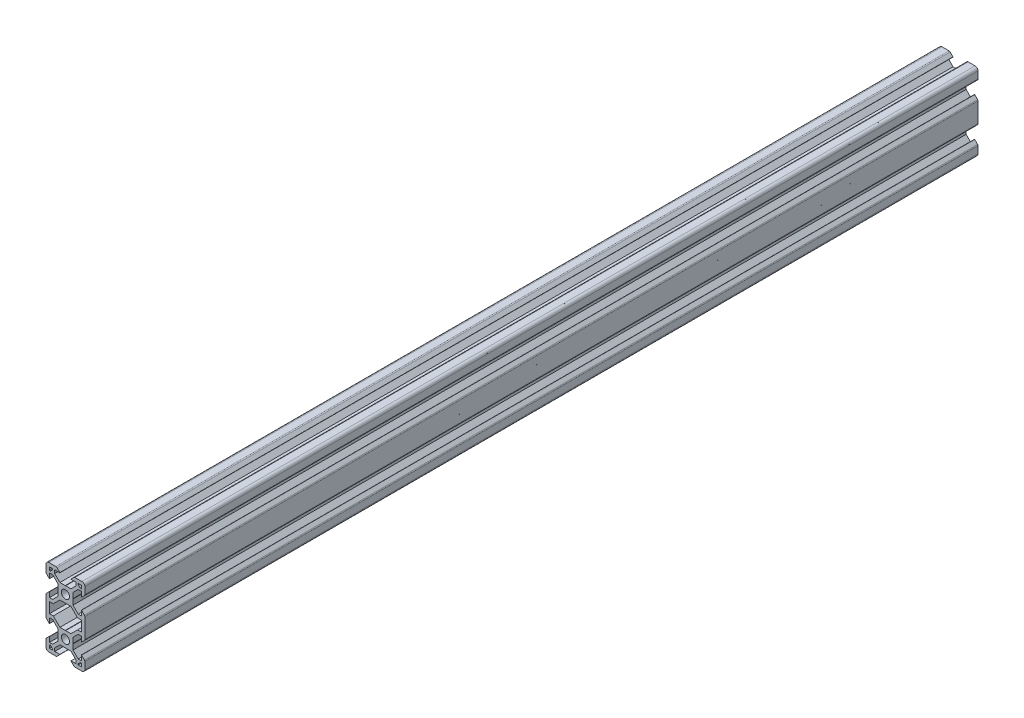
SolidWorks part; units mm, degrees
ref_plane "Front Plane" through (0, 0, 0) normal (0, 0, 1) x (1, 0, 0)
ref_plane "Top Plane" through (0, 0, 0) normal (0, 1, 0) x (1, 0, 0)
ref_plane "Right Plane" through (0, 0, 0) normal (1, 0, 0) x (0, 0, -1)
sketch "Sketch1" plane through (0, 0, 0) normal (0, 0, 1) x (1, 0, 0)
  line L0 (-8.2, 2.8875) -> (-8.2, 5.4975)
  line L3 (-4.9072, 9.9975) -> (-8.5, 9.9975)
  line L4 (-10, 4.9047) -> (-10, 8.4975)
  line L5 (-2.1, 0) -> (-3.8, 0) construction
  line L6 (0, 3.8) -> (0, 0) construction
  line L7 (-0.1, 3.9) -> (-2.8404, 3.9)
  line L8 (-3.9, 0.1) -> (-3.9, 2.8383)
  line L9 (-2.89, 8.1975) -> (-5.5, 8.1975)
  line L10 (-6.57, 8.1975) -> (-6.57, 7.6575)
  line L11 (-8.2, 6.5675) -> (-7.66, 6.5675)
  line L12 (-5.5, 8.1975) -> (-5.5, 6.5588)
  line L13 (-6.56, 5.4975) -> (-8.2, 5.4975)
  line L14 (-8.2, 8.1975) -> (-1.4852, 1.4847) construction
  line L15 (-6.56, 5.4975) -> (-3.9, 2.8383)
  line L16 (-5.5, 6.5588) -> (-2.8404, 3.9)
  line L17 (-7.66, 6.5675) -> (-6.57, 7.6575)
  line L18 (-8.7302, 7.6671) -> (-0.5302, -0.5304) construction
  line L19 (-7.6698, 8.7279) -> (0.5302, 0.5304) construction
  line L20 (-8.2, 8.1975) -> (0, 0) construction
  line L21 (-8.2, 6.5675) -> (-8.2, 8.1975)
  line L22 (-8.2, -0.0025) -> (-8.2, 8.1975) construction
  line L23 (-6.57, 8.1975) -> (-8.2, 8.1975)
  line L24 (0, 8.1975) -> (-8.2, 8.1975) construction
  line L25 (-10, -0.0025) -> (-10, 9.9975) construction
  line L26 (0, 9.9975) -> (-10, 9.9975) construction
  line L27 (-2.89, 8.3075) -> (-2.89, 8.1975)
  line L29 (-8.31, 2.8875) -> (-8.2, 2.8875)
  line L30 (-4.3486, 9.7661) -> (-2.89, 8.3075)
  line L31 (-8.31, 2.8875) -> (-9.7686, 4.3461)
  line L34 (-0.1, 3.9) -> (0, 3.8)
  line L35 (-3.9, 0.1) -> (-3.8, 0)
  line L36 (-8.2, -7.2996) -> (-6.24, -7.2996)
  line L37 (0, 0) -> (0, -10) construction
  line L38 (-0.1, -3.9) -> (-2.8404, -3.9)
  line L39 (-3.8, 0) -> (-3.9, -0.1)
  line L40 (-3.9, -0.1) -> (-3.9, -2.84)
  line L41 (-2.8404, -3.9) -> (-6.24, -7.2996)
  line L42 (-3.9, -2.84) -> (-6.56, -5.5)
  line L43 (-8.2, -2.89) -> (-8.2, -5.5)
  line L44 (-6.56, 5.4975) -> (-6.56, -5.5) construction
  line L45 (-6.56, -5.5) -> (-8.2, -5.5)
  line L46 (-0.1, -3.9) -> (0, -3.8)
  line L48 (-8.2, -2.89) -> (-8.31, -2.89)
  line L49 (-8.31, -2.89) -> (-9.7657, -4.3457)
  line L52 (-10, -10) -> (0, -10) construction
  line L53 (-8.2, -7.2996) -> (-8.2, -10)
  line L61 (-10, -4.9114) -> (-10, -10)
  arc A1 (-10, 8.4975) -> (-8.5, 9.9975) centre (-8.5, 8.4975) cw
  arc A2 (-9.7686, 4.3461) -> (-10, 4.9047) centre (-9.21, 4.9047) cw
  arc A3 (-4.3486, 9.7661) -> (-4.9072, 9.9975) centre (-4.9072, 9.2075) ccw
  arc A4 (-9.7657, -4.3457) -> (-10, -4.9114) centre (-9.2, -4.9114) ccw
  arc A6 (0, 2.1) -> (0, -2.1) centre (0, 0) ccw
  point P29 (-10, 9.9975)
  point P39 (-10, 4.5775)
  point P42 (-4.58, 9.9975)
  point P48 (-10, -4.58)
  dimension "D15" = 1.5
  dimension "D22" = 0.79
  dimension "D30" = 1.96
  dimension "D31" = 2.1
  dimension "D39" = 0.8
  dimension "D4" = 1.8
  dimension "D5" = 3.43
  dimension "D6" = 3.43
  dimension "D7" = 0.54
  dimension "D8" = 0.54
  dimension "D9" = 1.07
  dimension "D10" = 1.07
  dimension "D11" = 3.9
  dimension "D12" = 3.9
  dimension "D16" = 7.11
  dimension "D17" = 0.11
  dimension "D18" = 1.69
  dimension "D19" = 0.11
  dimension "D20" = 7.11
  dimension "D21" = 1.69
  dimension "D23" = 10
  dimension "D24" = 0.1
  dimension "D25" = 45
  dimension "D26" = 0.1
  dimension "D27" = 45
  dimension "D28" = 1.64
  dimension "D29" = 10
  dimension "D32" = 3.9
  dimension "D33" = 45
  dimension "D34" = 2.74
  dimension "D35" = 45
  dimension "D37" = 2.61
  dimension "D38" = 90
  dimension "D40" = 0.1
  dimension "D41" = 45
  dimension "D13" = 0.75
  dimension "D14" = 0.75
sketch "Sketch2" plane through (0, 0, 0) normal (0, 0, 1) x (1, 0, 0)
  line L0 (-0.1, 3.9) -> (0, 3.8) construction
  line L1 (-0.1, 3.9) -> (-2.8404, 3.9) construction
  line L2 (-5.5, 6.5588) -> (-2.8404, 3.9) construction
  line L3 (-5.5, 8.1975) -> (-5.5, 6.5588) construction
  line L4 (-2.89, 8.1975) -> (-5.5, 8.1975) construction
  line L5 (-7.66, 6.5675) -> (-6.57, 7.6575)
  line L6 (-6.57, 7.6575) -> (-6.57, 8.1975)
  line L7 (-6.57, 8.1975) -> (-8.2, 8.1975)
  line L8 (-8.2, 8.1975) -> (-8.2, 6.5675)
  line L9 (-8.2, 6.5675) -> (-7.66, 6.5675)
  line L10 (-7.66, 6.5675) -> (-6.57, 7.6575)
  line L11 (-6.57, 7.6575) -> (-6.57, 8.1975)
  line L12 (-6.57, 8.1975) -> (-8.2, 8.1975)
  line L13 (-8.2, 8.1975) -> (-8.2, 6.5675)
  line L14 (-8.2, 6.5675) -> (-7.66, 6.5675)
  line L15 (-2.89, 8.3075) -> (-2.89, 8.1975) construction
  line L16 (-4.3486, 9.7661) -> (-2.89, 8.3075) construction
  line L17 (-4.9072, 9.9975) -> (-8.5, 9.9975) construction
  line L18 (-10, 4.9047) -> (-10, 8.4975) construction
  line L19 (-8.31, 2.8875) -> (-9.7686, 4.3461) construction
  line L20 (-8.31, 2.8875) -> (-8.2, 2.8875) construction
  line L21 (-8.2, 2.8875) -> (-8.2, 5.4975) construction
  line L22 (-6.56, 5.4975) -> (-8.2, 5.4975) construction
  line L23 (-6.56, 5.4975) -> (-3.9, 2.8383) construction
  line L24 (-3.9, 0.1) -> (-3.9, 2.8383) construction
  line L25 (-3.9, 0.1) -> (-3.8, 0) construction
  line L26 (-3.8, 0) -> (-3.9, -0.1) construction
  line L27 (-3.9, -0.1) -> (-3.9, -2.84) construction
  line L28 (-3.9, -2.84) -> (-6.56, -5.5) construction
  line L29 (-6.56, -5.5) -> (-8.2, -5.5) construction
  line L30 (-8.2, -2.89) -> (-8.2, -5.5) construction
  line L31 (-8.2, -2.89) -> (-8.31, -2.89) construction
  line L32 (-8.31, -2.89) -> (-9.7657, -4.3457) construction
  line L33 (-10, -4.9114) -> (-10, -10) construction
  line L34 (-0.1, -3.9) -> (0, -3.8) construction
  line L35 (-0.1, -3.9) -> (-2.8404, -3.9) construction
  line L36 (-2.8404, -3.9) -> (-6.24, -7.2996) construction
  line L37 (-8.2, -7.2996) -> (-6.24, -7.2996) construction
  line L38 (-8.2, -7.2996) -> (-8.2, -10) construction
  line L39 (-0.1, 3.9) -> (0, 3.8)
  line L40 (-0.1, 3.9) -> (-2.8404, 3.9)
  line L41 (-5.5, 6.5588) -> (-2.8404, 3.9)
  line L42 (-5.5, 8.1975) -> (-5.5, 6.5588)
  line L43 (-2.89, 8.1975) -> (-5.5, 8.1975)
  line L44 (-2.89, 8.3075) -> (-2.89, 8.1975)
  line L45 (-4.3486, 9.7661) -> (-2.89, 8.3075)
  line L46 (-4.9072, 9.9975) -> (-8.5, 9.9975)
  line L47 (-10, 4.9047) -> (-10, 8.4975)
  line L48 (-8.31, 2.8875) -> (-9.7686, 4.3461)
  line L49 (-8.31, 2.8875) -> (-8.2, 2.8875)
  line L50 (-8.2, 2.8875) -> (-8.2, 5.4975)
  line L51 (-6.56, 5.4975) -> (-8.2, 5.4975)
  line L52 (-6.56, 5.4975) -> (-3.9, 2.8383)
  line L53 (-3.9, 0.1) -> (-3.9, 2.8383)
  line L54 (-3.9, 0.1) -> (-3.8, 0)
  line L55 (-3.8, 0) -> (-3.9, -0.1)
  line L56 (-3.9, -0.1) -> (-3.9, -2.84)
  line L57 (-3.9, -2.84) -> (-6.56, -5.5)
  line L58 (-6.56, -5.5) -> (-8.2, -5.5)
  line L59 (-8.2, -2.89) -> (-8.2, -5.5)
  line L60 (-8.2, -2.89) -> (-8.31, -2.89)
  line L61 (-8.31, -2.89) -> (-9.7657, -4.3457)
  line L62 (-10, -4.9114) -> (-10, -15.0886)
  line L63 (-0.1, -3.9) -> (0, -3.8)
  line L64 (-0.1, -3.9) -> (-2.8404, -3.9)
  line L65 (-2.8404, -3.9) -> (-6.24, -7.2996)
  line L66 (-8.2, -7.2996) -> (-6.24, -7.2996)
  line L67 (-8.2, -7.2996) -> (-8.2, -12.7004)
  line L68 (0, 0) -> (0, -10) construction
  line L69 (-10, -10) -> (0, -10) construction
  line L70 (0, 0) -> (0, -20) construction
  line L71 (-10, -10) -> (10, -10) construction
  line L72 (8.2, -7.2996) -> (8.2, -12.7004)
  line L73 (8.2, -7.2996) -> (6.24, -7.2996)
  line L74 (2.8404, -3.9) -> (6.24, -7.2996)
  line L75 (0.1, -3.9) -> (2.8404, -3.9)
  line L76 (0.1, -3.9) -> (0, -3.8)
  line L77 (10, -4.9114) -> (10, -15.0886)
  line L78 (8.31, -2.89) -> (9.7657, -4.3457)
  line L79 (8.2, -2.89) -> (8.31, -2.89)
  line L80 (8.2, -2.89) -> (8.2, -5.5)
  line L81 (6.56, -5.5) -> (8.2, -5.5)
  line L82 (3.9, -2.84) -> (6.56, -5.5)
  line L83 (3.9, -0.1) -> (3.9, -2.84)
  line L84 (3.8, 0) -> (3.9, -0.1)
  line L85 (3.9, 0.1) -> (3.8, 0)
  line L86 (3.9, 0.1) -> (3.9, 2.8383)
  line L87 (6.56, 5.4975) -> (3.9, 2.8383)
  line L88 (6.56, 5.4975) -> (8.2, 5.4975)
  line L89 (8.2, 2.8875) -> (8.2, 5.4975)
  line L90 (8.31, 2.8875) -> (8.2, 2.8875)
  line L91 (8.31, 2.8875) -> (9.7686, 4.3461)
  line L92 (10, 4.9047) -> (10, 8.4975)
  line L93 (4.9072, 9.9975) -> (8.5, 9.9975)
  line L94 (4.3486, 9.7661) -> (2.89, 8.3075)
  line L95 (2.89, 8.3075) -> (2.89, 8.1975)
  line L96 (2.89, 8.1975) -> (5.5, 8.1975)
  line L97 (5.5, 8.1975) -> (5.5, 6.5588)
  line L98 (5.5, 6.5588) -> (2.8404, 3.9)
  line L99 (0.1, 3.9) -> (2.8404, 3.9)
  line L100 (0.1, 3.9) -> (0, 3.8)
  line L101 (8.2, 6.5675) -> (7.66, 6.5675)
  line L102 (8.2, 8.1975) -> (8.2, 6.5675)
  line L103 (6.57, 8.1975) -> (8.2, 8.1975)
  line L104 (6.57, 7.6575) -> (6.57, 8.1975)
  line L105 (7.66, 6.5675) -> (6.57, 7.6575)
  line L106 (7.66, -26.5675) -> (6.57, -27.6575)
  line L107 (6.57, -27.6575) -> (6.57, -28.1975)
  line L108 (6.57, -28.1975) -> (8.2, -28.1975)
  line L109 (8.2, -28.1975) -> (8.2, -26.5675)
  line L110 (8.2, -26.5675) -> (7.66, -26.5675)
  line L111 (0.1, -23.9) -> (0, -23.8)
  line L112 (0.1, -23.9) -> (2.8404, -23.9)
  line L113 (5.5, -26.5588) -> (2.8404, -23.9)
  line L114 (5.5, -28.1975) -> (5.5, -26.5588)
  line L115 (2.89, -28.1975) -> (5.5, -28.1975)
  line L116 (2.89, -28.3075) -> (2.89, -28.1975)
  line L117 (4.3486, -29.7661) -> (2.89, -28.3075)
  line L118 (4.9072, -29.9975) -> (8.5, -29.9975)
  line L119 (10, -24.9047) -> (10, -28.4975)
  line L120 (8.31, -22.8875) -> (9.7686, -24.3461)
  line L121 (8.31, -22.8875) -> (8.2, -22.8875)
  line L122 (8.2, -22.8875) -> (8.2, -25.4975)
  line L123 (6.56, -25.4975) -> (8.2, -25.4975)
  line L124 (6.56, -25.4975) -> (3.9, -22.8383)
  line L125 (3.9, -20.1) -> (3.9, -22.8383)
  line L126 (3.9, -20.1) -> (3.8, -20)
  line L127 (3.8, -20) -> (3.9, -19.9)
  line L128 (3.9, -19.9) -> (3.9, -17.16)
  line L129 (3.9, -17.16) -> (6.56, -14.5)
  line L130 (6.56, -14.5) -> (8.2, -14.5)
  line L131 (8.2, -17.11) -> (8.2, -14.5)
  line L132 (8.2, -17.11) -> (8.31, -17.11)
  line L133 (8.31, -17.11) -> (9.7657, -15.6543)
  line L134 (0.1, -16.1) -> (0, -16.2)
  line L135 (0.1, -16.1) -> (2.8404, -16.1)
  line L136 (2.8404, -16.1) -> (6.24, -12.7004)
  line L137 (8.2, -12.7004) -> (6.24, -12.7004)
  line L138 (-8.2, -12.7004) -> (-6.24, -12.7004)
  line L139 (-2.8404, -16.1) -> (-6.24, -12.7004)
  line L140 (-0.1, -16.1) -> (-2.8404, -16.1)
  line L141 (-0.1, -16.1) -> (0, -16.2)
  line L142 (-8.31, -17.11) -> (-9.7657, -15.6543)
  line L143 (-8.2, -17.11) -> (-8.31, -17.11)
  line L144 (-8.2, -17.11) -> (-8.2, -14.5)
  line L145 (-6.56, -14.5) -> (-8.2, -14.5)
  line L146 (-3.9, -17.16) -> (-6.56, -14.5)
  line L147 (-3.9, -19.9) -> (-3.9, -17.16)
  line L148 (-3.8, -20) -> (-3.9, -19.9)
  line L149 (-3.9, -20.1) -> (-3.8, -20)
  line L150 (-3.9, -20.1) -> (-3.9, -22.8383)
  line L151 (-6.56, -25.4975) -> (-3.9, -22.8383)
  line L152 (-6.56, -25.4975) -> (-8.2, -25.4975)
  line L153 (-8.2, -22.8875) -> (-8.2, -25.4975)
  line L154 (-8.31, -22.8875) -> (-8.2, -22.8875)
  line L155 (-8.31, -22.8875) -> (-9.7686, -24.3461)
  line L156 (-10, -24.9047) -> (-10, -28.4975)
  line L157 (-4.9072, -29.9975) -> (-8.5, -29.9975)
  line L158 (-4.3486, -29.7661) -> (-2.89, -28.3075)
  line L159 (-2.89, -28.3075) -> (-2.89, -28.1975)
  line L160 (-2.89, -28.1975) -> (-5.5, -28.1975)
  line L161 (-5.5, -28.1975) -> (-5.5, -26.5588)
  line L162 (-5.5, -26.5588) -> (-2.8404, -23.9)
  line L163 (-0.1, -23.9) -> (-2.8404, -23.9)
  line L164 (-0.1, -23.9) -> (0, -23.8)
  line L165 (-8.2, -26.5675) -> (-7.66, -26.5675)
  line L166 (-8.2, -28.1975) -> (-8.2, -26.5675)
  line L167 (-6.57, -28.1975) -> (-8.2, -28.1975)
  line L168 (-6.57, -27.6575) -> (-6.57, -28.1975)
  line L169 (-7.66, -26.5675) -> (-6.57, -27.6575)
  arc A0 (0, 2.1) -> (0, -2.1) centre (0, 0) ccw construction
  arc A1 (-4.3486, 9.7661) -> (-4.9072, 9.9975) centre (-4.9072, 9.2075) ccw construction
  arc A2 (-8.5, 9.9975) -> (-10, 8.4975) centre (-8.5, 8.4975) ccw construction
  arc A3 (-10, 4.9047) -> (-9.7686, 4.3461) centre (-9.21, 4.9047) ccw construction
  arc A4 (-9.7657, -4.3457) -> (-10, -4.9114) centre (-9.2, -4.9114) ccw construction
  circle A5 centre (0, 0) radius 2.1
  arc A6 (-4.3486, 9.7661) -> (-4.9072, 9.9975) centre (-4.9072, 9.2075) ccw
  arc A7 (-8.5, 9.9975) -> (-10, 8.4975) centre (-8.5, 8.4975) ccw
  arc A8 (-10, 4.9047) -> (-9.7686, 4.3461) centre (-9.21, 4.9047) ccw
  arc A9 (-9.7657, -4.3457) -> (-10, -4.9114) centre (-9.2, -4.9114) ccw
  arc A10 (9.7657, -4.3457) -> (10, -4.9114) centre (9.2, -4.9114) cw
  arc A11 (10, 4.9047) -> (9.7686, 4.3461) centre (9.21, 4.9047) cw
  arc A12 (8.5, 9.9975) -> (10, 8.4975) centre (8.5, 8.4975) cw
  arc A13 (4.3486, 9.7661) -> (4.9072, 9.9975) centre (4.9072, 9.2075) cw
  arc A14 (4.3486, -29.7661) -> (4.9072, -29.9975) centre (4.9072, -29.2075) ccw
  arc A15 (8.5, -29.9975) -> (10, -28.4975) centre (8.5, -28.4975) ccw
  arc A16 (10, -24.9047) -> (9.7686, -24.3461) centre (9.21, -24.9047) ccw
  arc A17 (9.7657, -15.6543) -> (10, -15.0886) centre (9.2, -15.0886) ccw
  arc A18 (-9.7657, -15.6543) -> (-10, -15.0886) centre (-9.2, -15.0886) cw
  arc A19 (-10, -24.9047) -> (-9.7686, -24.3461) centre (-9.21, -24.9047) cw
  arc A20 (-8.5, -29.9975) -> (-10, -28.4975) centre (-8.5, -28.4975) cw
  arc A21 (-4.3486, -29.7661) -> (-4.9072, -29.9975) centre (-4.9072, -29.2075) cw
  circle A22 centre (0, -20) radius 2.1
  point P147 (8.2, -10)
  dimension "D1" = 0
extrude "Boss-Extrude1" add sketch "Sketch2" against normal blind 460
